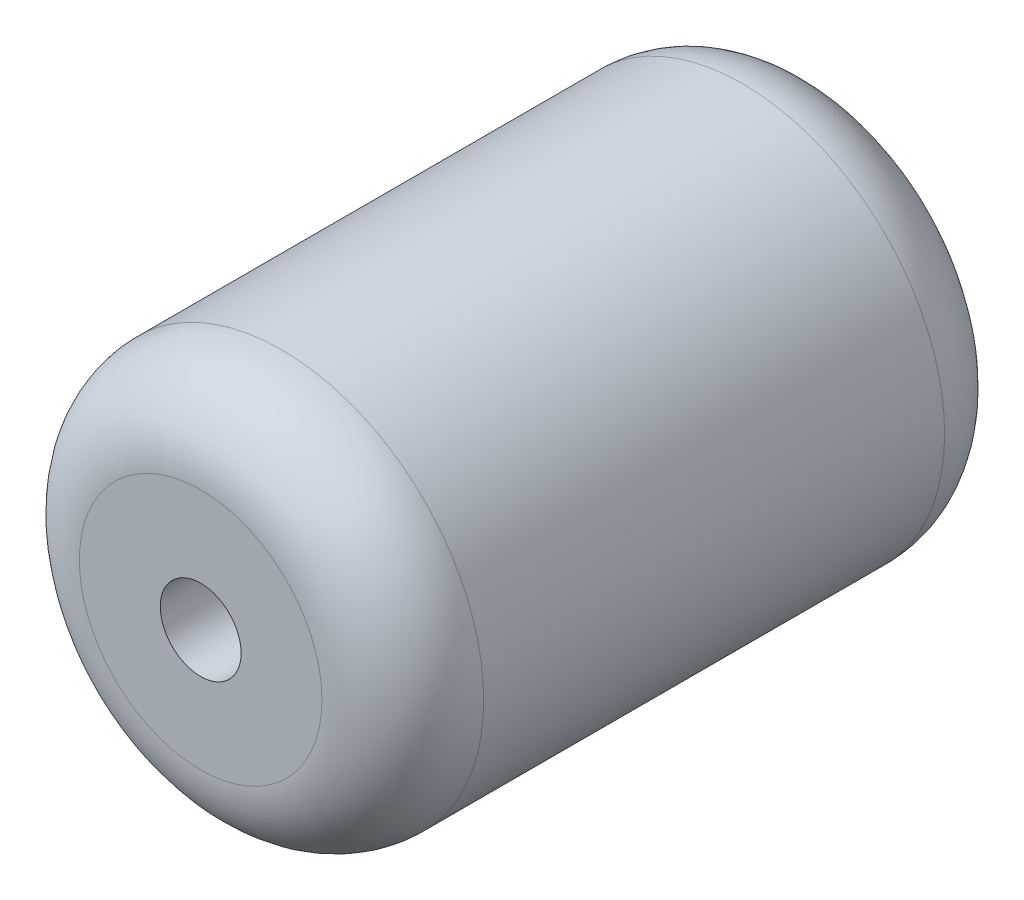
SolidWorks part; units mm, degrees
ref_plane "Alzado" through (0, 0, 0) normal (0, 0, 1) x (1, 0, 0)
ref_plane "Planta" through (0, 0, 0) normal (0, 1, 0) x (1, 0, 0)
ref_plane "Vista lateral" through (0, 0, 0) normal (1, 0, 0) x (0, 0, -1)
sketch "Croquis1" plane through (0, 0, 0) normal (0, 0, 1) x (1, 0, 0)
  circle A0 centre (0, 0) radius 25
  circle A1 centre (0, 0) radius 5
  dimension "D1" = 50
  dimension "D2" = 10
extrude "Saliente-Extruir1" add sketch "Croquis1" along normal blind 77
fillet "Redondeo1" radius 10 2 edges at (25, 0, 77) (25, 0, 0)
